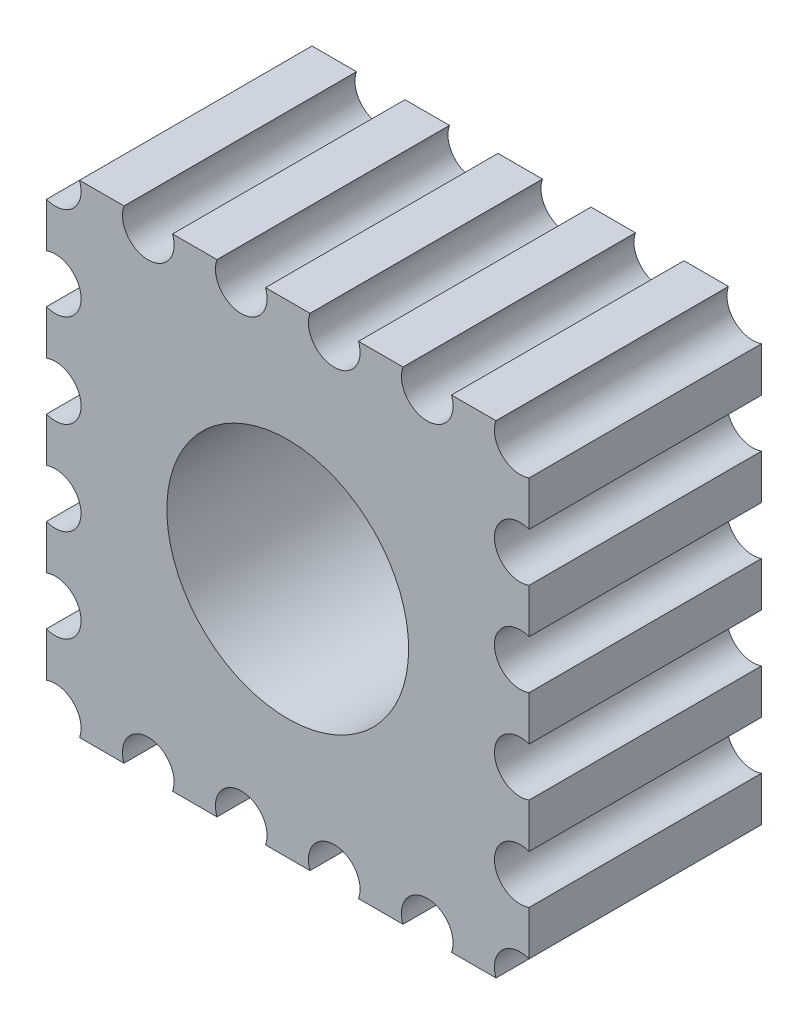
SolidWorks part; units mm, degrees
ref_plane "Front Plane" through (0, 0, 0) normal (0, 0, 1) x (1, 0, 0)
ref_plane "Top Plane" through (0, 0, 0) normal (0, 1, 0) x (1, 0, 0)
ref_plane "Right Plane" through (0, 0, 0) normal (1, 0, 0) x (0, 0, -1)
sketch "Sketch2" plane through (0, 0, 0) normal (0, 0, 1) x (1, 0, 0)
  line L0 (-8.1984, 4.754) -> (1.8016, -5.246) construction
  line L1 (-7.6769, 4.944) -> (-6.7198, 4.944)
  line L2 (-8.3884, 4.2325) -> (-8.3884, 3.2754)
  line L3 (-7.6769, -5.436) -> (-6.7198, -5.436)
  line L4 (1.9916, 4.2325) -> (1.9916, 3.2754)
  line L9 (-7.8059, -4.8536) -> (1.8016, 4.754) construction
  line L10 (-5.6769, 4.944) -> (-4.7198, 4.944)
  line L11 (-3.6769, 4.944) -> (-2.7198, 4.944)
  line L12 (-1.6769, 4.944) -> (-0.7198, 4.944)
  line L13 (0.3231, 4.944) -> (1.2802, 4.944)
  line L14 (1.9916, 2.2325) -> (1.9916, 1.2754)
  line L15 (1.9916, 0.2325) -> (1.9916, -0.7246)
  line L16 (1.9916, -1.7675) -> (1.9916, -2.7246)
  line L17 (1.9916, -3.7675) -> (1.9916, -4.7246)
  line L18 (0.3231, -5.436) -> (1.2802, -5.436)
  line L19 (-1.6769, -5.436) -> (-0.7198, -5.436)
  line L20 (-3.6769, -5.436) -> (-2.7198, -5.436)
  line L21 (-5.6769, -5.436) -> (-4.7198, -5.436)
  line L22 (-8.3884, -3.7675) -> (-8.3884, -4.7246)
  line L23 (-8.3884, -1.7675) -> (-8.3884, -2.7246)
  line L24 (-8.3884, 0.2325) -> (-8.3884, -0.7246)
  line L25 (-8.3884, 2.2325) -> (-8.3884, 1.2754)
  arc A0 (-8.3884, 4.2325) -> (-7.6769, 4.944) centre (-8.1984, 4.754) ccw
  arc A1 (-6.7198, 4.944) -> (-5.6769, 4.944) centre (-6.1984, 4.754) ccw
  arc A2 (-4.7198, 4.944) -> (-3.6769, 4.944) centre (-4.1984, 4.754) ccw
  arc A3 (-2.7198, 4.944) -> (-1.6769, 4.944) centre (-2.1984, 4.754) ccw
  arc A4 (-0.7198, 4.944) -> (0.3231, 4.944) centre (-0.1984, 4.754) ccw
  arc A5 (1.2802, 4.944) -> (1.9916, 4.2325) centre (1.8016, 4.754) ccw
  arc A6 (1.9916, 3.2754) -> (1.9916, 2.2325) centre (1.8016, 2.754) ccw
  arc A7 (1.9916, 1.2754) -> (1.9916, 0.2325) centre (1.8016, 0.754) ccw
  arc A8 (1.9916, -0.7246) -> (1.9916, -1.7675) centre (1.8016, -1.246) ccw
  arc A9 (1.9916, -2.7246) -> (1.9916, -3.7675) centre (1.8016, -3.246) ccw
  arc A10 (1.9916, -4.7246) -> (1.2802, -5.436) centre (1.8016, -5.246) ccw
  arc A11 (0.3231, -5.436) -> (-0.7198, -5.436) centre (-0.1984, -5.246) ccw
  arc A12 (-1.6769, -5.436) -> (-2.7198, -5.436) centre (-2.1984, -5.246) ccw
  arc A13 (-3.6769, -5.436) -> (-4.7198, -5.436) centre (-4.1984, -5.246) ccw
  arc A14 (-5.6769, -5.436) -> (-6.7198, -5.436) centre (-6.1984, -5.246) ccw
  arc A15 (-7.6769, -5.436) -> (-8.3884, -4.7246) centre (-8.1984, -5.246) ccw
  arc A16 (-8.3884, -3.7675) -> (-8.3884, -2.7246) centre (-8.1984, -3.246) ccw
  arc A17 (-8.3884, -1.7675) -> (-8.3884, -0.7246) centre (-8.1984, -1.246) ccw
  arc A18 (-8.3884, 0.2325) -> (-8.3884, 1.2754) centre (-8.1984, 0.754) ccw
  arc A19 (-8.3884, 2.2325) -> (-8.3884, 3.2754) centre (-8.1984, 2.754) ccw
  circle A20 centre (-3.1984, -0.246) radius 4.1
  circle A21 centre (-3.1984, -0.246) radius 2.6
  dimension "D7" = 6
  dimension "D8" = 6
  dimension "D9" = 6
  dimension "D10" = 5
extrude "Boss-Extrude1" add sketch "Sketch2" along normal blind 5 contours A20 A21 | A19 L25 A18 L24 A17 L23 A16 L22 A15 L3 A14 L21 A13 L20 A12 L19 A11 L18 A10 L17 A9 L16 A8 L15 A7 L14 A6 L4 A5 L13 A4 L12 A3 L11 A2 L10 A1 L1 A0 L2 A20
